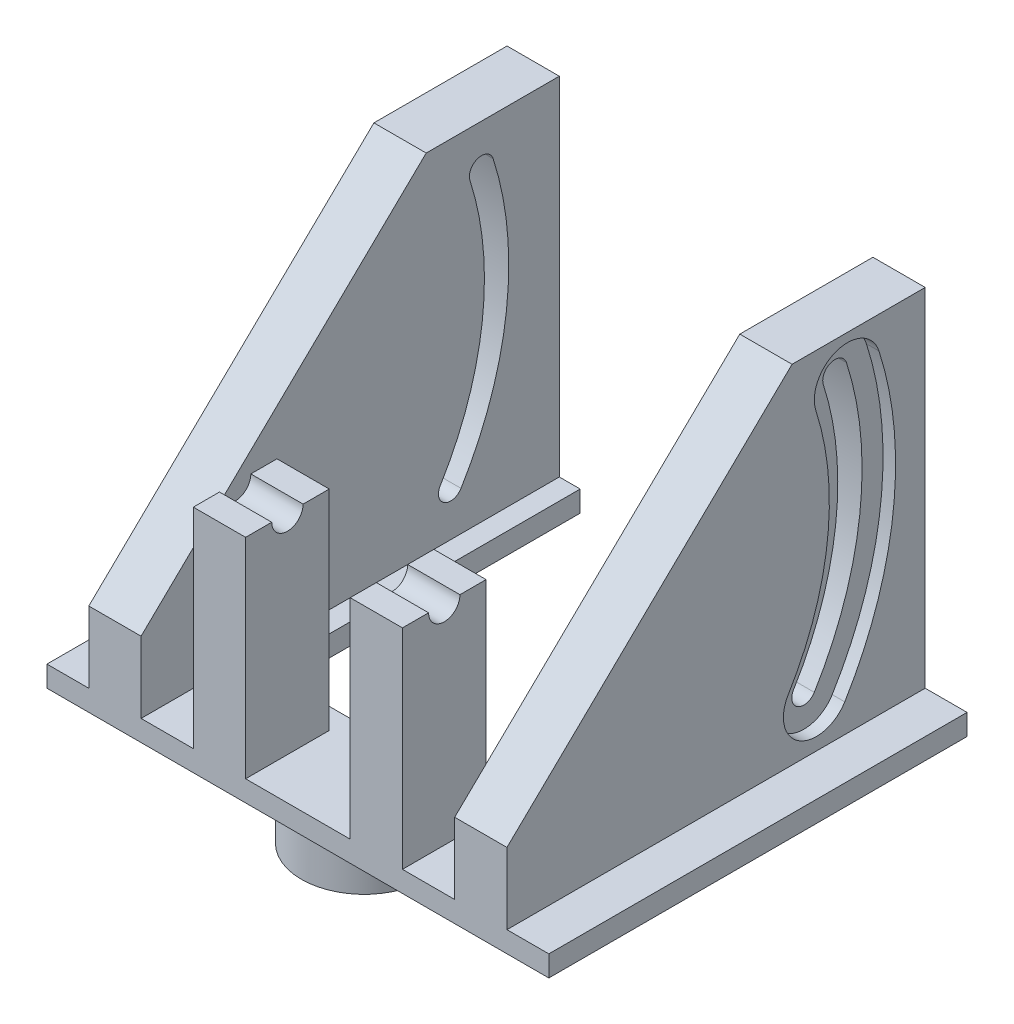
SolidWorks part; units mm, degrees
ref_plane "Front" through (0, 0, 0) normal (0, 0, 1) x (1, 0, 0)
ref_plane "Top" through (0, 0, 0) normal (0, 1, 0) x (1, 0, 0)
ref_plane "Right" through (0, 0, 0) normal (1, 0, 0) x (0, 0, -1)
sketch "Skizze1" plane through (0, 0, 0) normal (0, 1, 0) x (1, 0, 0)
  line L0 (120, 200) -> (120, 0) construction
  line L1 (0, 0) -> (240, 0)
  line L2 (0, 0) -> (0, 200)
  line L3 (0, 200) -> (55, 200)
  line L4 (240, 0) -> (240, 200)
  line L5 (55, 200) -> (55, 50)
  line L6 (55, 50) -> (185, 50)
  line L7 (185, 200) -> (185, 50)
  line L8 (185, 200) -> (240, 200)
  point P11 (120, 50)
  dimension "D1" = 200
  dimension "D2" = 240
  dimension "D3" = 130
  dimension "D4" = 50
extrude "Aufsatz-Linear austragen1" add sketch "Skizze1" along normal blind 10
sketch "Skizze2" plane through (0, 10, 0) normal (0, 1, 0) x (1, 0, 0)
  line L0 (215.5352, 20) -> (24.4648, 20) construction
  line L2 (170, 0) -> (170, 40)
  line L3 (170, 40) -> (145, 40)
  line L4 (145, 40) -> (145, 0)
  line L5 (170, 0) -> (145, 0)
  line L7 (120, 20) -> (120, 0) construction
  line L12 (120, 20) -> (120, 125.0317) construction
  line L13 (70, 0) -> (95, 0)
  line L14 (95, 40) -> (95, 0)
  line L15 (70, 40) -> (95, 40)
  line L16 (70, 0) -> (70, 40)
  line L17 (0, 0) -> (240, 0) construction
  point P9 (170, 20)
  point P10 (145, 20)
  point P18 (95, 20)
  point P19 (70, 20)
  dimension "D1" = 25
  dimension "D2" = 50
  dimension "D3" = 40
  dimension "D4" = 191.0705
extrude "Aufsatz-Linear austragen2" add sketch "Skizze2" along normal blind 100
sketch "Skizze3" plane through (170, 0, 0) normal (1, 0, 0) x (0, 0, -1)
  line L0 (0, 110) -> (40, 110) construction
  circle A0 centre (20, 110) radius 7.5
  dimension "D1" = 15
extrude "Schnitt-Linear austragen1" cut sketch "Skizze3" against normal through all
sketch "Skizze4" plane through (0, 10, 0) normal (0, 1, 0) x (1, 0, 0)
  line L0 (194.9782, 0) -> (194.9782, 200)
  line L1 (240, 200) -> (185, 200) construction
  line L2 (194.9782, 200) -> (219.9782, 200)
  line L3 (219.9782, 200) -> (219.9782, 0)
  line L4 (170, 0) -> (240, 0) construction
  line L5 (219.9782, 0) -> (194.9782, 0)
  line L6 (120, 50) -> (120, 192.7656) construction
  line L7 (185, 50) -> (55, 50) construction
  line L8 (20.0218, 0) -> (45.0218, 0)
  line L9 (20.0218, 200) -> (20.0218, 0)
  line L10 (45.0218, 200) -> (20.0218, 200)
  line L11 (45.0218, 0) -> (45.0218, 200)
  dimension "D1" = 25
extrude "Aufsatz-Linear austragen3" add sketch "Skizze4" along normal blind 200
sketch "Skizze7" plane through (219.9782, 0, 0) normal (1, 0, 0) x (0, 0, -1)
  line L0 (0, 44.0694) -> (136.3379, 175.9753)
  line L1 (0, 210) -> (0, 10) construction
  line L2 (136.3379, 175.9753) -> (200, 175.9753)
  line L3 (200, 210) -> (200, 10) construction
  line L4 (200, 175.9753) -> (200, 225.6225)
  line L5 (200, 225.6225) -> (-41.808, 225.6225)
  line L6 (-41.808, 225.6225) -> (0, 44.0694)
extrude "Schnitt-Linear austragen4" cut sketch "Skizze7" against normal up to next
ref_plane "Ebene1" through (120, 0, 0) normal (1, 0, 0) x (0, 0, -1)
sketch "Skizze6" plane through (219.9782, 0, 0) normal (1, 0, 0) x (0, 0, -1)
  line L0 (0, 10) -> (200, 10) construction
  arc A0 (131.8034, 10) -> (169.9716, 107.0816) centre (20, 110) ccw construction
  arc A1 (148.0233, 31.8333) -> (162.8136, 155.8723) centre (20, 110) ccw construction
  arc A2 (152.9859, 28.8033) -> (168.3496, 157.6504) centre (20, 110) ccw
  arc A3 (143.0607, 34.8633) -> (157.2777, 154.0941) centre (20, 110) ccw
  arc A4 (143.0607, 34.8633) -> (152.9859, 28.8033) centre (148.0233, 31.8333) ccw
  arc A5 (168.3496, 157.6504) -> (157.2777, 154.0941) centre (162.8136, 155.8723) ccw
  point P8 (168.9449, 92.2399)
  dimension "D1" = 150
extrude "Schnitt-Linear austragen3" cut sketch "Skizze6" against normal through all
sketch "Skizze8" plane through (219.9782, 0, 0) normal (1, 0, 0) x (0, 0, -1)
  arc A0 (148.0233, 31.8333) -> (162.8136, 155.8723) centre (20, 110) ccw construction
  arc A1 (161.539, 23.5811) -> (177.8908, 160.7151) centre (20, 110) ccw
  arc A2 (134.5076, 40.0855) -> (147.7365, 151.0295) centre (20, 110) ccw
  arc A3 (134.5076, 40.0855) -> (161.539, 23.5811) centre (148.0233, 31.8333) ccw
  arc A4 (177.8908, 160.7151) -> (147.7365, 151.0295) centre (162.8136, 155.8723) ccw
  arc A5 (152.9859, 28.8033) -> (168.3496, 157.6504) centre (20, 110) ccw construction
  point P3 (168.9449, 92.2399)
extrude "Schnitt-Linear austragen5" cut sketch "Skizze8" against normal blind 6
mirror "Spiegeln1" about plane through (120, 0, 0) normal (1, 0, 0) of "Schnitt-Linear austragen5", "Schnitt-Linear austragen4"
sketch "Skizze9" plane through (0, 0, 0) normal (0, -1, 0) x (1, 0, 0)
  line L0 (120, 0) -> (120, -50) construction
  line L1 (0, 0) -> (240, 0) construction
  line L2 (185, -50) -> (55, -50) construction
  circle A0 centre (120, -31.686) radius 30
  dimension "D1" = 60
extrude "Aufsatz-Linear austragen4" add sketch "Skizze9" along normal blind 20
sketch "Skizze10" plane through (0, 0, 0) normal (0, -1, 0) x (1, 0, 0)
  circle A0 centre (120, -31.686) radius 51
  dimension "D1" = 102
extrude "Aufsatz-Linear austragen5" [suppressed] add sketch "Skizze10" along normal blind 1
